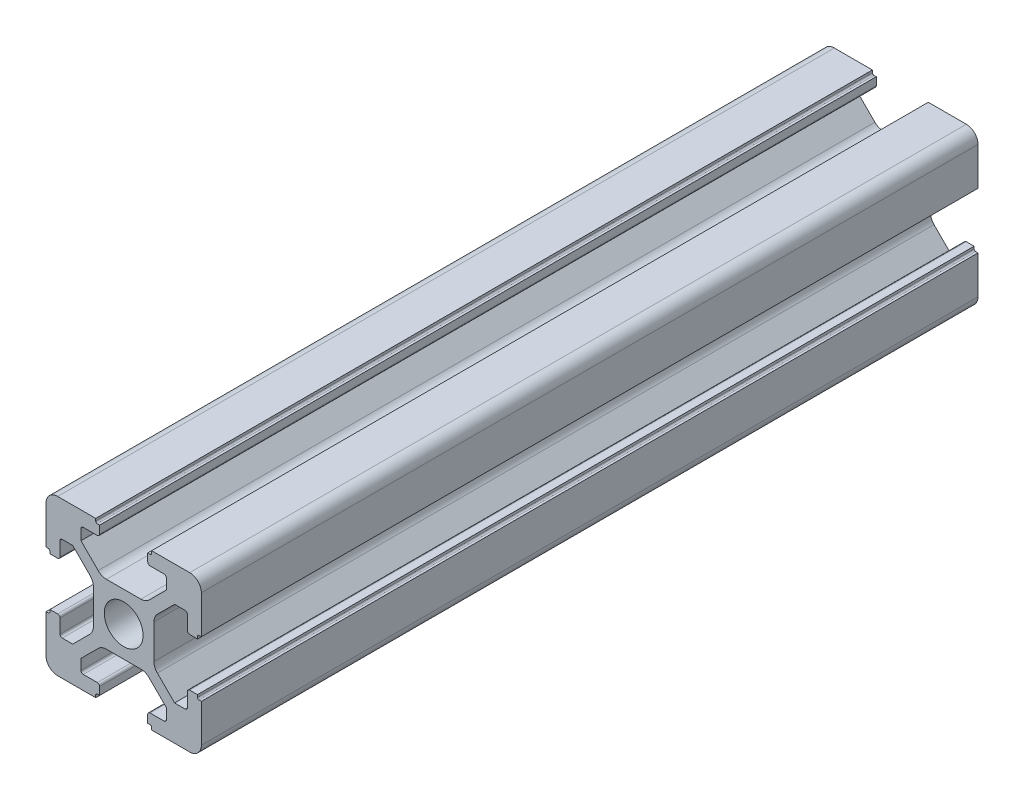
SolidWorks part; units mm, degrees
ref_plane "前视基准面" through (0, 0, 0) normal (0, 0, 1) x (1, 0, 0)
ref_plane "上视基准面" through (0, 0, 0) normal (0, 1, 0) x (1, 0, 0)
ref_plane "右视基准面" through (0, 0, 0) normal (1, 0, 0) x (0, 0, -1)
sketch "草图1" plane through (0, 0, 0) normal (0, 0, 1) x (1, 0, 0)
  line L0 (4.216, 3.2442) -> (6.4367, 5.4649)
  line L1 (6.4367, 5.4649) -> (7.7767, 5.4649)
  line L2 (8.0767, 5.1649) -> (8.0767, 3.3649)
  line L3 (8.3767, 3.0649) -> (9.3767, 3.0649)
  line L4 (9.3767, 3.0649) -> (9.3767, 3.3649)
  line L5 (9.5767, 3.5649) -> (9.8767, 3.5649)
  line L6 (9.8767, 3.5649) -> (9.8767, 8.4649)
  line L7 (8.3767, 9.9649) -> (3.4767, 9.9649)
  line L8 (3.4767, 9.9649) -> (3.4767, 9.6649)
  line L9 (3.2767, 9.4649) -> (2.9767, 9.4649)
  line L10 (2.9767, 9.4649) -> (2.9767, 8.4649)
  line L11 (3.2767, 8.1649) -> (5.0767, 8.1649)
  line L12 (5.3767, 7.8649) -> (5.3767, 6.5249)
  line L13 (5.3767, 6.5249) -> (3.156, 4.3042)
  line L14 (2.0953, 3.8649) -> (-2.342, 3.8649)
  line L15 (-3.4027, 4.3042) -> (-5.6233, 6.5249)
  line L16 (-5.6233, 6.5249) -> (-5.6233, 7.8649)
  line L17 (-5.3233, 8.1649) -> (-3.5233, 8.1649)
  line L18 (-3.2233, 8.4649) -> (-3.2233, 9.4649)
  line L19 (-3.2233, 9.4649) -> (-3.5233, 9.4649)
  line L20 (-3.7233, 9.6649) -> (-3.7233, 9.9649)
  line L21 (-3.7233, 9.9649) -> (-8.6233, 9.9649)
  line L22 (-10.1233, 8.4649) -> (-10.1233, 3.5649)
  line L23 (-10.1233, 3.5649) -> (-9.8233, 3.5649)
  line L24 (-9.6233, 3.3649) -> (-9.6233, 3.0649)
  line L25 (-9.6233, 3.0649) -> (-8.6233, 3.0649)
  line L26 (-8.3233, 3.3649) -> (-8.3233, 5.1649)
  line L27 (-8.0233, 5.4649) -> (-6.6833, 5.4649)
  line L28 (-6.6833, 5.4649) -> (-4.4627, 3.2442)
  line L29 (-4.0233, 2.1836) -> (-4.0233, -2.2538)
  line L30 (-4.4627, -3.3144) -> (-6.6833, -5.5351)
  line L31 (-6.6833, -5.5351) -> (-8.0233, -5.5351)
  line L32 (-8.3233, -5.2351) -> (-8.3233, -3.4351)
  line L33 (-8.6233, -3.1351) -> (-9.6233, -3.1351)
  line L34 (-9.6233, -3.1351) -> (-9.6233, -3.4351)
  line L35 (-9.8233, -3.6351) -> (-10.1233, -3.6351)
  line L36 (-10.1233, -3.6351) -> (-10.1233, -8.5351)
  line L37 (-8.6233, -10.0351) -> (-3.7233, -10.0351)
  line L38 (-3.7233, -10.0351) -> (-3.7233, -9.7351)
  line L39 (-3.5233, -9.5351) -> (-3.2233, -9.5351)
  line L40 (-3.2233, -9.5351) -> (-3.2233, -8.5351)
  line L41 (-3.5233, -8.2351) -> (-5.3233, -8.2351)
  line L42 (-5.6233, -7.9351) -> (-5.6233, -6.5951)
  line L43 (-5.6233, -6.5951) -> (-3.4027, -4.3744)
  line L44 (-2.342, -3.9351) -> (2.0953, -3.9351)
  line L45 (3.156, -4.3744) -> (5.3767, -6.5951)
  line L46 (5.3767, -6.5951) -> (5.3767, -7.9351)
  line L47 (5.0767, -8.2351) -> (3.2767, -8.2351)
  line L48 (2.9767, -8.5351) -> (2.9767, -9.5351)
  line L49 (2.9767, -9.5351) -> (3.2767, -9.5351)
  line L50 (3.4767, -9.7351) -> (3.4767, -10.0351)
  line L51 (3.4767, -10.0351) -> (8.3767, -10.0351)
  line L52 (9.8767, -8.5351) -> (9.8767, -3.6351)
  line L53 (9.8767, -3.6351) -> (9.5767, -3.6351)
  line L54 (9.3767, -3.4351) -> (9.3767, -3.1351)
  line L55 (9.3767, -3.1351) -> (8.3767, -3.1351)
  line L56 (8.0767, -3.4351) -> (8.0767, -5.2351)
  line L57 (7.7767, -5.5351) -> (6.4367, -5.5351)
  line L58 (6.4367, -5.5351) -> (4.216, -3.3144)
  line L59 (3.7767, -2.2538) -> (3.7767, 2.1836)
  circle A0 centre (-0.1233, -0.0351) radius 2.5
  arc A1 (8.0767, 5.1649) -> (7.7767, 5.4649) centre (7.7767, 5.1649) ccw
  arc A2 (8.0767, 3.3649) -> (8.3767, 3.0649) centre (8.3767, 3.3649) ccw
  arc A3 (9.5767, 3.5649) -> (9.3767, 3.3649) centre (9.5767, 3.3649) ccw
  arc A4 (9.8767, 8.4649) -> (8.3767, 9.9649) centre (8.3767, 8.4649) ccw
  arc A5 (3.2767, 9.4649) -> (3.4767, 9.6649) centre (3.2767, 9.6649) ccw
  arc A6 (2.9767, 8.4649) -> (3.2767, 8.1649) centre (3.2767, 8.4649) ccw
  arc A7 (5.3767, 7.8649) -> (5.0767, 8.1649) centre (5.0767, 7.8649) ccw
  arc A8 (2.0953, 3.8649) -> (3.156, 4.3042) centre (2.0953, 5.3649) ccw
  arc A9 (-3.4027, 4.3042) -> (-2.342, 3.8649) centre (-2.342, 5.3649) ccw
  arc A10 (-5.3233, 8.1649) -> (-5.6233, 7.8649) centre (-5.3233, 7.8649) ccw
  arc A11 (-3.5233, 8.1649) -> (-3.2233, 8.4649) centre (-3.5233, 8.4649) ccw
  arc A12 (-3.7233, 9.6649) -> (-3.5233, 9.4649) centre (-3.5233, 9.6649) ccw
  arc A13 (-8.6233, 9.9649) -> (-10.1233, 8.4649) centre (-8.6233, 8.4649) ccw
  arc A14 (-9.6233, 3.3649) -> (-9.8233, 3.5649) centre (-9.8233, 3.3649) ccw
  arc A15 (-8.6233, 3.0649) -> (-8.3233, 3.3649) centre (-8.6233, 3.3649) ccw
  arc A16 (-8.0233, 5.4649) -> (-8.3233, 5.1649) centre (-8.0233, 5.1649) ccw
  arc A17 (-4.0233, 2.1836) -> (-4.4627, 3.2442) centre (-5.5233, 2.1836) ccw
  arc A18 (-4.4627, -3.3144) -> (-4.0233, -2.2538) centre (-5.5233, -2.2538) ccw
  arc A19 (-8.3233, -5.2351) -> (-8.0233, -5.5351) centre (-8.0233, -5.2351) ccw
  arc A20 (-8.3233, -3.4351) -> (-8.6233, -3.1351) centre (-8.6233, -3.4351) ccw
  arc A21 (-9.8233, -3.6351) -> (-9.6233, -3.4351) centre (-9.8233, -3.4351) ccw
  arc A22 (-10.1233, -8.5351) -> (-8.6233, -10.0351) centre (-8.6233, -8.5351) ccw
  arc A23 (-3.5233, -9.5351) -> (-3.7233, -9.7351) centre (-3.5233, -9.7351) ccw
  arc A24 (-3.2233, -8.5351) -> (-3.5233, -8.2351) centre (-3.5233, -8.5351) ccw
  arc A25 (-5.6233, -7.9351) -> (-5.3233, -8.2351) centre (-5.3233, -7.9351) ccw
  arc A26 (-2.342, -3.9351) -> (-3.4027, -4.3744) centre (-2.342, -5.4351) ccw
  arc A27 (3.156, -4.3744) -> (2.0953, -3.9351) centre (2.0953, -5.4351) ccw
  arc A28 (5.0767, -8.2351) -> (5.3767, -7.9351) centre (5.0767, -7.9351) ccw
  arc A29 (3.2767, -8.2351) -> (2.9767, -8.5351) centre (3.2767, -8.5351) ccw
  arc A30 (3.4767, -9.7351) -> (3.2767, -9.5351) centre (3.2767, -9.7351) ccw
  arc A31 (8.3767, -10.0351) -> (9.8767, -8.5351) centre (8.3767, -8.5351) ccw
  arc A32 (9.3767, -3.4351) -> (9.5767, -3.6351) centre (9.5767, -3.4351) ccw
  arc A33 (8.3767, -3.1351) -> (8.0767, -3.4351) centre (8.3767, -3.4351) ccw
  arc A34 (7.7767, -5.5351) -> (8.0767, -5.2351) centre (7.7767, -5.2351) ccw
  arc A35 (3.7767, -2.2538) -> (4.216, -3.3144) centre (5.2767, -2.2538) ccw
  arc A36 (4.216, 3.2442) -> (3.7767, 2.1836) centre (5.2767, 2.1836) ccw
extrude "凸台-拉伸1" add sketch "草图1" along normal blind 100
